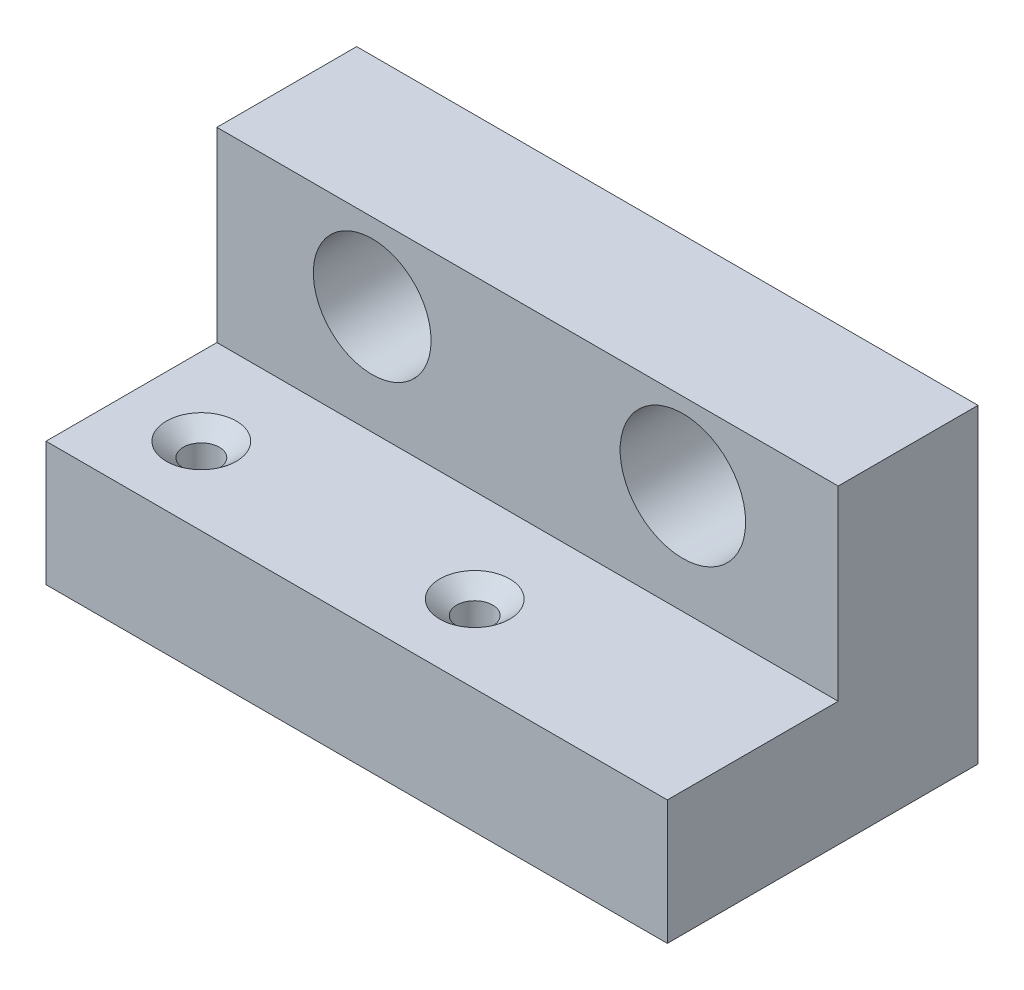
SolidWorks part; units mm, degrees
material "ABS"
ref_plane "Front Plane" through (0, 0, 0) normal (0, 0, 1) x (1, 0, 0)
ref_plane "Top Plane" through (0, 0, 0) normal (0, 1, 0) x (1, 0, 0)
ref_plane "Right Plane" through (0, 0, 0) normal (1, 0, 0) x (0, 0, -1)
sketch "Sketch1" plane through (0, 0, 0) normal (0, 0, 1) x (1, 0, 0)
  line L0 (0, 0) -> (50.8, 0)
  line L1 (50.8, 0) -> (50.8, 25.4)
  line L2 (50.8, 25.4) -> (0, 25.4)
  line L3 (0, 25.4) -> (0, 0)
  circle A0 centre (12.7, 19.05) radius 4.8133
  circle A1 centre (38.1, 19.05) radius 5.1308
  dimension "D5" = 25.4
  dimension "D6" = 10.2616
  dimension "D7" = 9.6266
  dimension "D1" = 50.8
  dimension "D2" = 25.4
  dimension "D3" = 19.05
  dimension "D4" = 12.7
extrude "Boss-Extrude1" add sketch "Sketch1" along normal blind 11.43
sketch "Sketch2" plane through (0, 0, 0) normal (0, 1, 0) x (1, 0, 0)
  line L0 (0, 0) -> (0, -25.4)
  line L1 (0, -25.4) -> (50.8, -25.4)
  line L2 (50.8, -25.4) -> (50.8, 0)
  line L3 (-30.0886, 0) -> (30.0886, 0) construction
  line L4 (0, 0) -> (50.8, 0)
  point P4 (6.35, -19.05)
  point P8 (35.052, -19.05)
  dimension "D1" = 50.8
  dimension "D2" = 25.4
  dimension "D3" = 28.702
  dimension "D4" = 19.05
  dimension "D5" = 6.35
extrude "Boss-Extrude2" add sketch "Sketch2" along normal blind 10.16
sketch "Sketch4" plane through (0, 10.16, 0) normal (0, 1, 0) x (1, 0, 0)
  line L0 (0, 0) -> (0, -25.4)
  line L1 (0, -25.4) -> (50.8, -25.4)
  line L2 (50.8, -25.4) -> (50.8, 0)
  line L3 (0, 0) -> (50.8, 0)
  point P3 (6.35, -19.05)
  point P5 (28.702, -19.05)
  dimension "D1" = 50.8
  dimension "D2" = 25.4
  dimension "D3" = 28.702
  dimension "D4" = 19.05
  dimension "D5" = 6.35
hole_wizard "CSK for #4 Flat Head Machine Screw (100)1" positions "Sketch4" profile "Sketch5" countersink size "#4" standard "ANSI Inch" end condition through all
sketch "Sketch5" plane through (28.702, 10.16, 19.05) normal (1, 0, 0) x (0, 0, 1)
  line L0 (0, 0) -> (0, 10.16)
  line L1 (0, 10.16) -> (1.4732, 10.16)
  line L2 (1.4732, 10.16) -> (1.4732, 1.1616)
  line L3 (1.4732, 1.1616) -> (2.8575, 0)
  line L5 (2.8575, 0) -> (0, 0)
  line L6 (-1.4732, 1.1616) -> (-2.8575, 0) construction
  line L11 (0, -6.35) -> (0, 107.95) construction
  dimension "Thru Hole Dia." = 2.9464
  dimension "Thru Hole Depth" = 10.16
  dimension "Near C'Sink Dia." = 5.715
  dimension "Near C'Sink Angle" = 100
